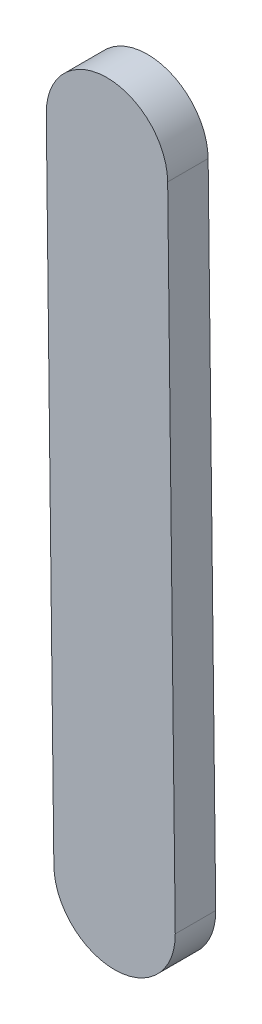
SolidWorks part; units mm, degrees
ref_plane "前视基准面" through (0, 0, 0) normal (0, 0, 1) x (1, 0, 0)
ref_plane "上视基准面" through (0, 0, 0) normal (0, 1, 0) x (1, 0, 0)
ref_plane "右视基准面" through (0, 0, 0) normal (1, 0, 0) x (0, 0, -1)
other "Configuration Table"
sketch "草图1" plane through (0, 0, 0) normal (0, 0, 1) x (1, 0, 0)
  line L0 (-31.2842, 61.4662) -> (-31.0967, 45.4673) construction
  line L1 (-29.7843, 61.4838) -> (-29.5968, 45.4849)
  line L2 (-32.7841, 61.4486) -> (-32.5966, 45.4497)
  arc A0 (-29.7843, 61.4838) -> (-32.7841, 61.4486) centre (-31.2842, 61.4662) ccw
  arc A1 (-32.5966, 45.4497) -> (-29.5968, 45.4849) centre (-31.0967, 45.4673) ccw
  point P2 (-31.1904, 53.4668)
extrude "凸台-拉伸1" add sketch "草图1" along normal blind 1
